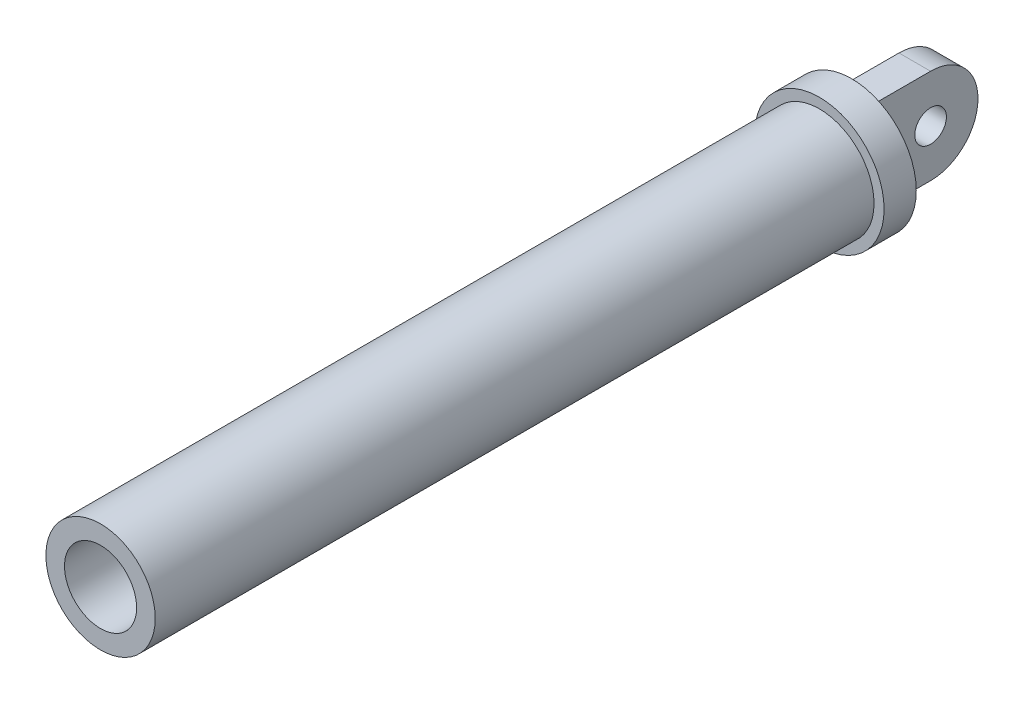
SolidWorks part; units mm, degrees
ref_plane "Front Plane" through (0, 0, 0) normal (0, 0, 1) x (1, 0, 0)
ref_plane "Top Plane" through (0, 0, 0) normal (0, 1, 0) x (1, 0, 0)
ref_plane "Right Plane" through (0, 0, 0) normal (1, 0, 0) x (0, 0, -1)
sketch "Sketch1" plane through (0, 0, 0) normal (1, 0, 0) x (0, 0, -1)
  line L1 (0, 15) -> (-20, 15)
  line L2 (0, 5) -> (0, -5)
  line L3 (0, -15) -> (-20, -15)
  line L4 (-20, 15) -> (-20, -15)
  circle A0 centre (0, 0) radius 5
  arc A1 (0, -15) -> (0, 15) centre (0, 0) ccw
  dimension "D1" = 30
  dimension "D2" = 10
  dimension "D3" = 20
extrude "Boss-Extrude1" add sketch "Sketch1" along normal mid plane 10 contours L3 A1 L1 L4 A0
sketch "Sketch2" plane through (0, 0, 0) normal (1, 0, 0) x (0, 0, -1)
  line L0 (-20, 0) -> (-20, 20.4746)
  line L1 (-20, 15) -> (-20, -15) construction
  line L2 (-20, 20.4746) -> (-30.1746, 20.4746)
  line L3 (-30.1746, 20.4746) -> (-30.1746, 17.2892)
  line L4 (-30.1746, 17.2892) -> (-257.531, 17.2892)
  line L7 (-257.531, 17.2892) -> (-257.531, 11.4085)
  line L8 (-257.531, 11.4085) -> (-34.3383, 11.4085)
  line L9 (-34.3383, 11.4085) -> (-34.3383, 0)
  line L10 (-34.3383, 0) -> (-20, 0)
revolve "Revolve1" add sketch "Sketch2" angle 360 about L10
